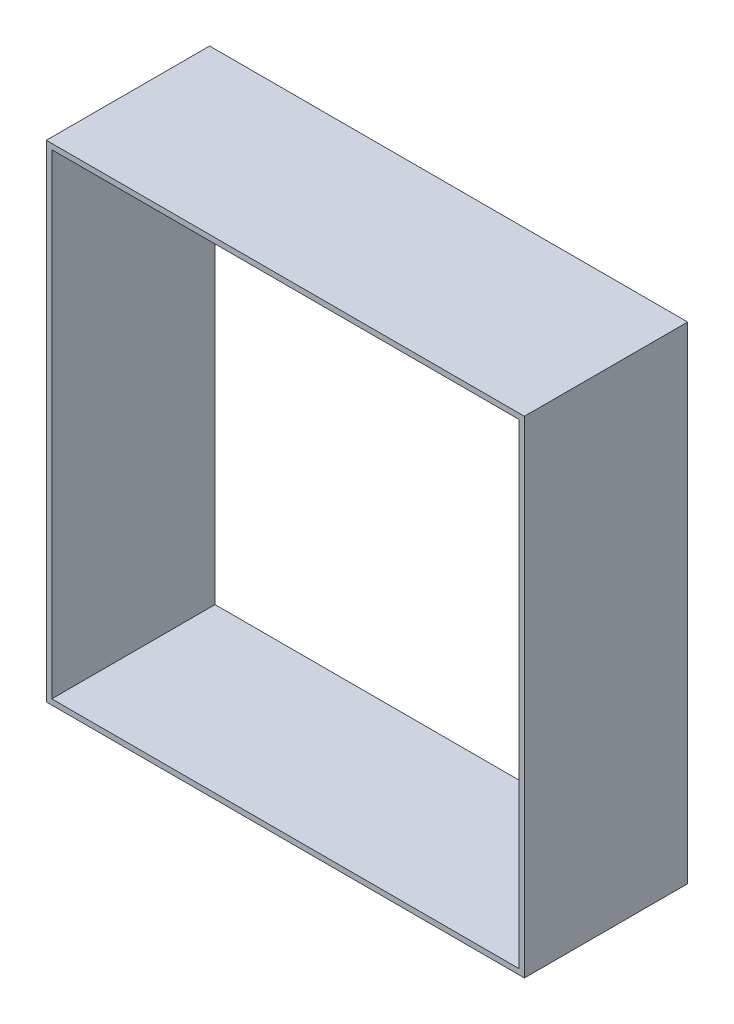
SolidWorks part; units mm, degrees
ref_plane "Front Plane" through (0, 0, 0) normal (0, 0, 1) x (1, 0, 0)
ref_plane "Top Plane" through (0, 0, 0) normal (0, 1, 0) x (1, 0, 0)
ref_plane "Right Plane" through (0, 0, 0) normal (1, 0, 0) x (0, 0, -1)
sketch "Sketch1" plane through (0, 0, 0) normal (0, 0, 1) x (1, 0, 0)
  line L0 (41.725, 43.5) -> (-41.725, 43.5) construction
  line L1 (42.925, -43.7) -> (-42.925, -43.7)
  line L2 (42.925, -43.7) -> (42.925, 43.7)
  line L3 (42.925, 43.7) -> (-42.925, 43.7)
  line L4 (-42.925, -43.7) -> (-42.925, 43.7)
  line L5 (42.925, -43.7) -> (-42.925, 43.7) construction
  line L6 (42.925, 43.7) -> (-42.925, -43.7) construction
  line L7 (-42.725, 42.5) -> (-42.725, 0) construction
  line L9 (-43.925, 44.7) -> (43.925, 44.7)
  line L10 (-43.925, 44.7) -> (-43.925, -44.7)
  line L11 (-43.925, -44.7) -> (43.925, -44.7)
  line L12 (43.925, 44.7) -> (43.925, -44.7)
  line L13 (-43.925, 44.7) -> (43.925, -44.7) construction
  line L14 (-43.925, -44.7) -> (43.925, 44.7) construction
  point P0 (0, 0)
  point P10 (0, 0)
  dimension "D1" = 0.2
  dimension "D2" = 0.2
  dimension "D3" = 1
  dimension "D4" = 1
extrude "Boss-Extrude1" add sketch "Sketch1" along normal mid plane 30
